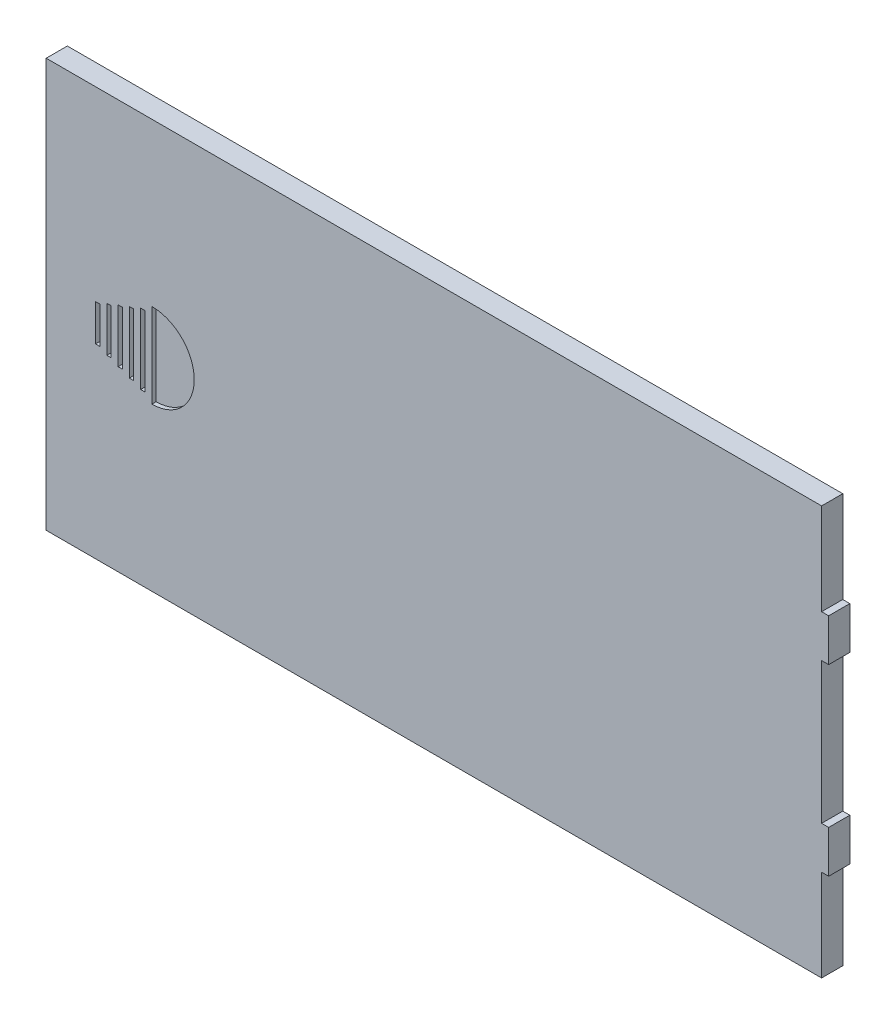
SolidWorks part; units mm, degrees
ref_plane "前视基准面" through (0, 0, 0) normal (0, 0, 1) x (1, 0, 0)
ref_plane "上视基准面" through (0, 0, 0) normal (0, 1, 0) x (1, 0, 0)
ref_plane "右视基准面" through (0, 0, 0) normal (1, 0, 0) x (0, 0, -1)
sketch "草图1" plane through (0, 0, 0) normal (0, 0, 1) x (1, 0, 0)
  line L0 (27.5, 8) -> (28, 8)
  line L1 (-27.5, 14.5) -> (27.5, 14.5)
  line L2 (-27.5, 14.5) -> (-27.5, -14.5)
  line L3 (-27.5, -14.5) -> (27.5, -14.5)
  line L4 (27.5, 14.5) -> (27.5, 8)
  line L5 (-27.5, 14.5) -> (27.5, -14.5) construction
  line L6 (-27.5, -14.5) -> (27.5, 14.5) construction
  line L7 (28, 8) -> (28, 5)
  line L8 (28, 5) -> (27.5, 5)
  line L9 (0, 0) -> (8.8744, 0) construction
  line L10 (28, -5) -> (27.5, -5)
  line L11 (28, -8) -> (28, -5)
  line L12 (27.5, -8) -> (28, -8)
  line L13 (27.5, 5) -> (27.5, -5)
  line L14 (27.5, -8) -> (27.5, -14.5)
  point P0 (0, 0)
  point P5 (-27.5, 0)
  dimension "D1" = 29
  dimension "D2" = 55
  dimension "D3" = 0.5
  dimension "D4" = 5
  dimension "D5" = 3
extrude "凸台-拉伸1" add sketch "草图1" along normal blind 1.5
sketch "草图2" plane through (0, 0, 1.5) normal (0, 0, 1) x (1, 0, 0)
  line L0 (-20, 3) -> (-20, -3)
  line L1 (-20, 0) -> (0, 0) construction
  line L3 (-20.5, -2.5) -> (-20.8, -2.5)
  line L4 (-20.5, -2.5) -> (-20.5, 2.5)
  line L5 (-20.5, 2.5) -> (-20.8, 2.5)
  line L6 (-20.8, -2.5) -> (-20.8, 2.5)
  line L7 (-20.5, -2.5) -> (-20.8, 2.5) construction
  line L8 (-20.5, 2.5) -> (-20.8, -2.5) construction
  line L9 (-21.3, -2.2) -> (-21.6, -2.2)
  line L10 (-21.3, -2.2) -> (-21.3, 2.2)
  line L11 (-21.3, 2.2) -> (-21.6, 2.2)
  line L12 (-21.6, -2.2) -> (-21.6, 2.2)
  line L13 (-21.3, -2.2) -> (-21.6, 2.2) construction
  line L14 (-21.3, 2.2) -> (-21.6, -2.2) construction
  line L15 (-22.1, -1.9) -> (-22.4, -1.9)
  line L16 (-22.1, -1.9) -> (-22.1, 1.9)
  line L17 (-22.1, 1.9) -> (-22.4, 1.9)
  line L18 (-22.4, -1.9) -> (-22.4, 1.9)
  line L19 (-22.1, -1.9) -> (-22.4, 1.9) construction
  line L20 (-22.1, 1.9) -> (-22.4, -1.9) construction
  line L21 (-22.9, -1.6) -> (-23.2, -1.6)
  line L22 (-22.9, -1.6) -> (-22.9, 1.6)
  line L23 (-22.9, 1.6) -> (-23.2, 1.6)
  line L24 (-23.2, -1.6) -> (-23.2, 1.6)
  line L25 (-22.9, -1.6) -> (-23.2, 1.6) construction
  line L26 (-22.9, 1.6) -> (-23.2, -1.6) construction
  line L27 (-23.7, -1.3) -> (-24, -1.3)
  line L28 (-23.7, -1.3) -> (-23.7, 1.3)
  line L29 (-23.7, 1.3) -> (-24, 1.3)
  line L30 (-24, -1.3) -> (-24, 1.3)
  line L31 (-23.7, -1.3) -> (-24, 1.3) construction
  line L32 (-23.7, 1.3) -> (-24, -1.3) construction
  arc A0 (-20, -3) -> (-20, 3) centre (-20, 0) ccw
  point P1 (-20.65, 0)
  point P10 (-21.45, 0)
  point P15 (-22.25, 0)
  point P20 (-23.05, 0)
  point P25 (-23.85, 0)
  dimension "D1" = 3
  dimension "D2" = 20
  dimension "D3" = 0.3
  dimension "D4" = 5
  dimension "D5" = 0.5
  dimension "D6" = 0.5
  dimension "D7" = 0.5
  dimension "D8" = 0.5
  dimension "D9" = 0.5
  dimension "D10" = 0.3
  dimension "D11" = 0.3
  dimension "D12" = 0.3
  dimension "D13" = 0.3
extrude "切除-拉伸1" cut sketch "草图2" against normal blind 0.3
